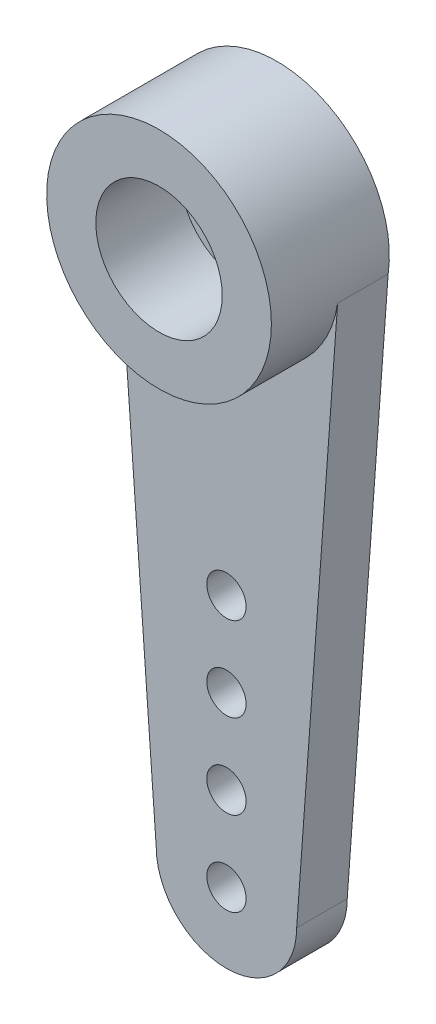
SolidWorks part; units mm, degrees
ref_plane "Plano frontal" through (0, 0, 0) normal (0, 0, 1) x (1, 0, 0)
ref_plane "Plano superior" through (0, 0, 0) normal (0, 1, 0) x (1, 0, 0)
ref_plane "Plano direito" through (0, 0, 0) normal (1, 0, 0) x (0, 0, -1)
sketch "Esboço1" plane through (0, 0, 0) normal (0, 0, 1) x (1, 0, 0)
  circle A0 centre (0, 0) radius 4
  circle A1 centre (0, 0) radius 2.25
  dimension "D1" = 8
  dimension "D2" = 4.5
extrude "Ressalto-extrusão1" add sketch "Esboço1" along normal blind 4.2
ref_plane "Plano1" through (0, 0, 0) normal (0, 0, 1) x (1, 0, 0)
sketch "Esboço3" plane through (0, 0, 0) normal (0, 0, 1) x (1, 0, 0)
  line L0 (2.5, -20.566) -> (4, 0)
  line L1 (-2.5, -20.566) -> (-4, 0)
  arc A0 (-2.5, -20.566) -> (2.5, -20.566) centre (0, -20.566) ccw
  circle A1 centre (0, 0) radius 4 construction
  circle A2 centre (0, -20.566) radius 0.7
  circle A3 centre (0, -17.566) radius 0.7
  circle A4 centre (0, -14.566) radius 0.7
  circle A5 centre (0, -11.566) radius 0.7
  arc A6 (-4, 0) -> (4, 0) centre (0, 0) ccw
extrude "Ressalto-extrusão2" add sketch "Esboço3" along normal blind 1.8 contours A6 L1 A0 L0 A5 A4 A3 A2
sketch "Esboço4" plane through (0, 0, 0) normal (0, 0, 1) x (1, 0, 0)
  circle A0 centre (0, 0) radius 2.5
extrude "Ressalto-extrusão3" add sketch "Esboço4" along normal blind 1.2
